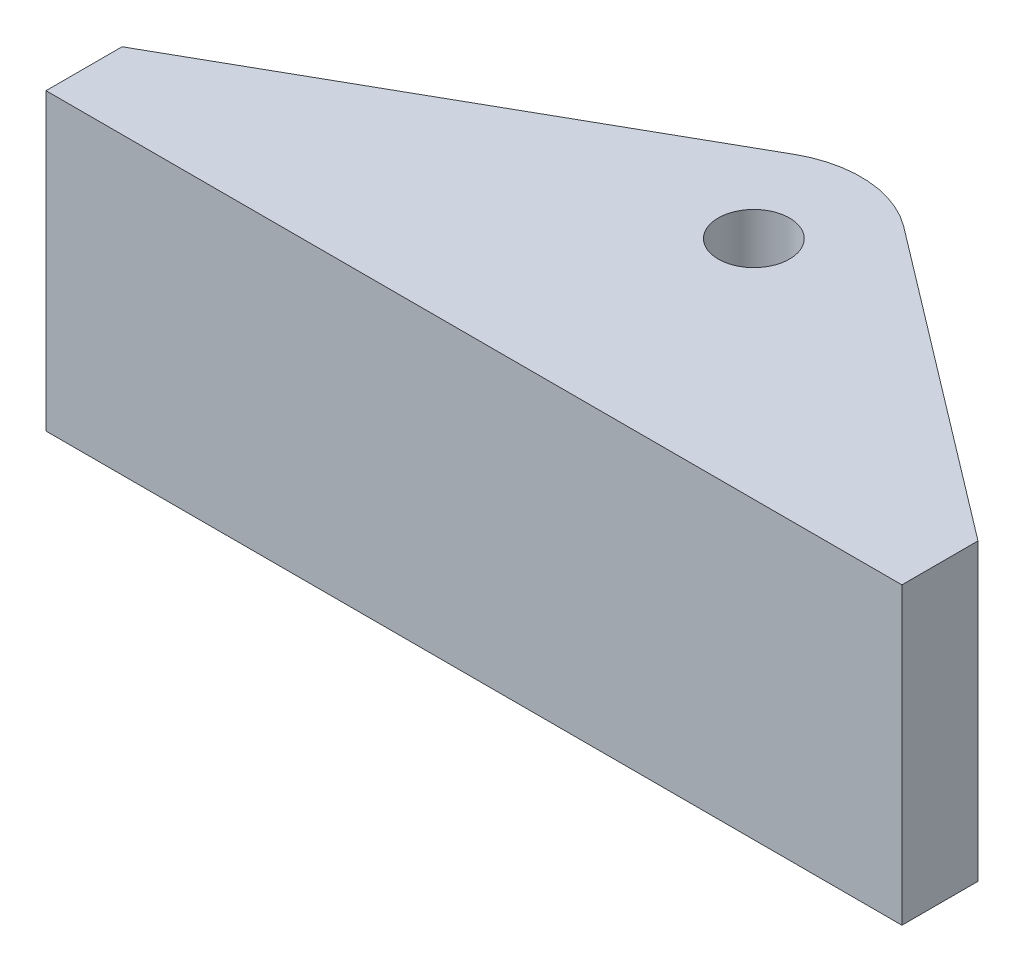
SolidWorks part; units mm, degrees
material "Cast Alloy Steel"
ref_plane "Front Plane" through (0, 0, 0) normal (0, 0, 1) x (1, 0, 0)
ref_plane "Top Plane" through (0, 0, 0) normal (0, 1, 0) x (1, 0, 0)
ref_plane "Right Plane" through (0, 0, 0) normal (1, 0, 0) x (0, 0, -1)
sketch "Sketch1" plane through (0, 0, 0) normal (0, 1, 0) x (1, 0, 0)
  line L0 (0, 5.08) -> (28.6638, 21.2987)
  line L1 (0, 0) -> (57.15, 0)
  line L2 (0, 0) -> (0, 5.08)
  line L4 (57.15, 0) -> (57.15, 5.08)
  line L5 (57.15, 5.08) -> (36.504, 20.7691)
  circle A0 centre (32.1818, 15.0813) radius 2.3812
  arc A1 (36.504, 20.7691) -> (28.6638, 21.2987) centre (32.1818, 15.0813) ccw
  dimension "D1" = 57.15
  dimension "D2" = 4.7625
  dimension "D5" = 24.9682
  dimension "D6" = 4.7625
  dimension "D3" = 15.0812
  dimension "D4" = 5.08
extrude "Boss-Extrude1" add sketch "Sketch1" against normal blind 19.685
